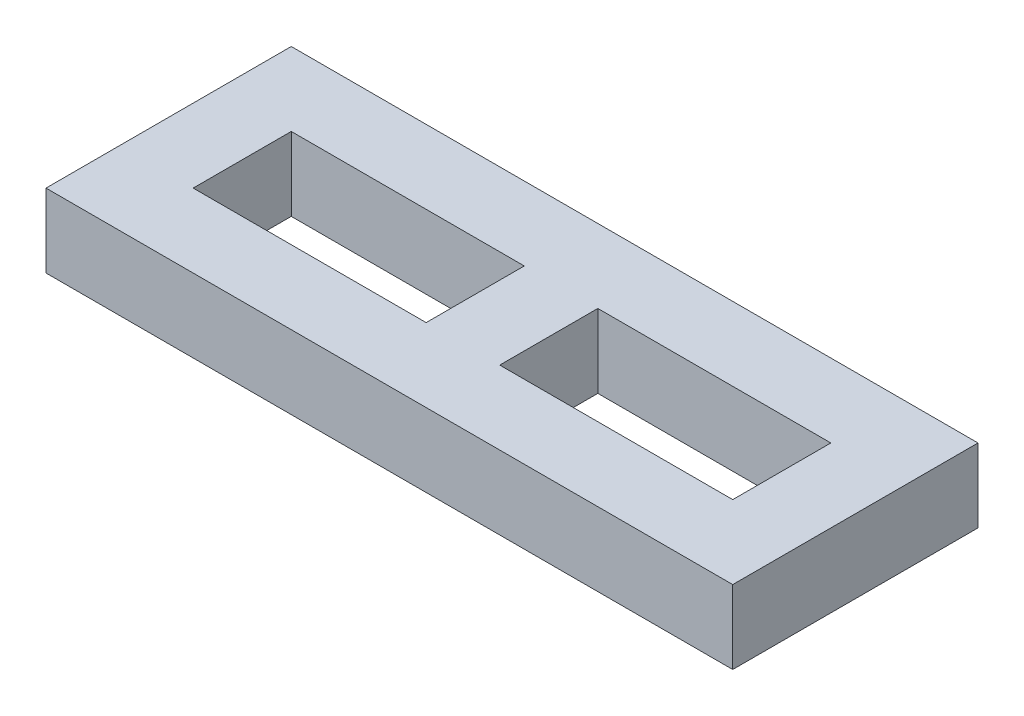
SolidWorks part; units mm, degrees
ref_plane "Front Plane" through (0, 0, 0) normal (0, 0, 1) x (1, 0, 0)
ref_plane "Top Plane" through (0, 0, 0) normal (0, 1, 0) x (1, 0, 0)
ref_plane "Right Plane" through (0, 0, 0) normal (1, 0, 0) x (0, 0, -1)
sketch "Sketch1" plane through (0, 0, 0) normal (1, 0, 0) x (0, 0, -1)
  line L1 (-31.75, -9.525) -> (31.75, -9.525)
  line L2 (-31.75, -9.525) -> (-31.75, 9.525)
  line L3 (-31.75, 9.525) -> (31.75, 9.525)
  line L4 (31.75, -9.525) -> (31.75, 9.525)
  line L5 (-31.75, -9.525) -> (31.75, 9.525) construction
  line L6 (-31.75, 9.525) -> (31.75, -9.525) construction
  point P0 (0, 0)
  dimension "D1" = 63.5
  dimension "D2" = 19.05
extrude "Boss-Extrude1" add sketch "Sketch1" along normal mid plane 177.8
sketch "Sketch2" [suppressed] plane through (0, 0, 0) normal (1, 0, 0) x (0, 0, -1)
  line L0 (-9.525, 9.525) -> (9.525, -9.525)
  line L1 (31.75, 9.525) -> (-31.75, 9.525) construction
  line L2 (-31.75, -9.525) -> (31.75, -9.525) construction
  dimension "D1" = 45
extrude "Cut-Extrude1" [suppressed] cut sketch "Sketch2" against normal through all and the other way through all flip side to cut
sketch "Sketch3" [suppressed] plane through (0, 9.525, 0) normal (0, 1, 0) x (1, 0, 0)
  line L0 (279.4, 0) -> (260.35, 0) construction
  line L1 (-260.35, 10.3187) -> (-171.45, 10.3188)
  line L2 (-260.35, 10.3187) -> (-260.35, -10.3187)
  line L3 (-260.35, -10.3187) -> (-171.45, -10.3188)
  line L4 (-171.45, 10.3188) -> (-171.45, -10.3188)
  line L5 (-152.4, 10.3188) -> (-63.5, 10.3188)
  line L6 (-152.4, 10.3188) -> (-152.4, -10.3188)
  line L7 (-152.4, -10.3188) -> (-63.5, -10.3188)
  line L8 (-63.5, 10.3188) -> (-63.5, -10.3188)
  line L9 (-44.45, 10.3188) -> (44.45, 10.3188)
  line L10 (-44.45, 10.3188) -> (-44.45, -10.3188)
  line L11 (-44.45, -10.3188) -> (44.45, -10.3188)
  line L12 (44.45, 10.3188) -> (44.45, -10.3188)
  line L13 (63.5, 10.3188) -> (152.4, 10.3188)
  line L14 (63.5, 10.3188) -> (63.5, -10.3188)
  line L15 (63.5, -10.3188) -> (152.4, -10.3188)
  line L16 (152.4, 10.3188) -> (152.4, -10.3188)
  line L17 (171.45, 10.3188) -> (260.35, 10.3187)
  line L18 (171.45, 10.3188) -> (171.45, -10.3188)
  line L19 (171.45, -10.3188) -> (260.35, -10.3187)
  line L20 (260.35, 10.3187) -> (260.35, -10.3187)
  line L21 (279.4, 29.3688) -> (279.4, -29.3687) construction
  line L22 (260.35, 0) -> (171.45, 0) construction
  line L23 (171.45, 0) -> (152.4, 0) construction
  line L24 (152.4, 0) -> (63.5, 0) construction
  line L25 (63.5, 0) -> (44.45, 0) construction
  line L26 (44.45, 0) -> (-44.45, 0) construction
  line L27 (-44.45, 0) -> (-63.5, 0) construction
  line L28 (-63.5, 0) -> (-152.4, 0) construction
  line L29 (-152.4, 0) -> (-171.45, 0) construction
  line L30 (-171.45, 0) -> (-260.35, 0) construction
  line L31 (-260.35, 0) -> (-279.4, 0) construction
  line L32 (-279.4, 29.3688) -> (-279.4, -29.3687) construction
  line L33 (215.9, 10.3188) -> (215.9, 29.3688) construction
  line L34 (279.4, 29.3688) -> (-279.4, 29.3688) construction
  dimension "D1" = 19.05
extrude "Cut-Extrude2" [suppressed] cut sketch "Sketch3" against normal through all
sketch "Sketch4" [suppressed] plane through (0, 9.525, 0) normal (0, 1, 0) x (1, 0, 0)
  line L0 (107.95, 0) -> (88.9, 0) construction
  line L1 (-88.9, 12.7) -> (-9.525, 12.7)
  line L2 (-88.9, 12.7) -> (-88.9, -12.7)
  line L3 (-88.9, -12.7) -> (-9.525, -12.7)
  line L4 (-9.525, 12.7) -> (-9.525, -12.7)
  line L5 (88.9, 12.7) -> (9.525, 12.7)
  line L6 (88.9, 12.7) -> (88.9, -12.7)
  line L7 (88.9, -12.7) -> (9.525, -12.7)
  line L8 (9.525, 12.7) -> (9.525, -12.7)
  line L9 (107.95, 31.75) -> (107.95, -31.75) construction
  line L10 (88.9, 0) -> (9.525, 0) construction
  line L11 (9.525, 0) -> (-9.525, 0) construction
  line L12 (-9.525, 0) -> (-88.9, 0) construction
  line L13 (-88.9, 0) -> (-107.95, 0) construction
  line L14 (-107.95, 31.75) -> (-107.95, -31.75) construction
  line L16 (-49.2125, 12.7) -> (-49.2125, 31.75) construction
  line L17 (107.95, 31.75) -> (-107.95, 31.75) construction
  dimension "D1" = 19.05
extrude "Cut-Extrude3" [suppressed] cut sketch "Sketch4" against normal through all
sketch "Sketch5" plane through (0, 9.525, 0) normal (0, 1, 0) x (1, 0, 0)
  line L0 (-88.9, 0) -> (-69.85, 0) construction
  line L1 (-69.85, 12.7) -> (-9.525, 12.7)
  line L2 (-69.85, 12.7) -> (-69.85, -12.7)
  line L3 (-69.85, -12.7) -> (-9.525, -12.7)
  line L4 (-9.525, 12.7) -> (-9.525, -12.7)
  line L5 (9.525, 12.7) -> (69.85, 12.7)
  line L6 (9.525, 12.7) -> (9.525, -12.7)
  line L7 (9.525, -12.7) -> (69.85, -12.7)
  line L8 (69.85, 12.7) -> (69.85, -12.7)
  line L9 (-88.9, 31.75) -> (-88.9, -31.75) construction
  line L10 (-69.85, 0) -> (-9.525, 0) construction
  line L11 (-9.525, 0) -> (9.525, 0) construction
  line L12 (9.525, 0) -> (69.85, 0) construction
  line L13 (69.85, 0) -> (88.9, 0) construction
  line L14 (88.9, 31.75) -> (88.9, -31.75) construction
  line L16 (39.6875, 12.7) -> (39.6875, 31.75) construction
  line L17 (88.9, 31.75) -> (-88.9, 31.75) construction
  dimension "D1" = 19.05
extrude "Cut-Extrude4" cut sketch "Sketch5" against normal through all
